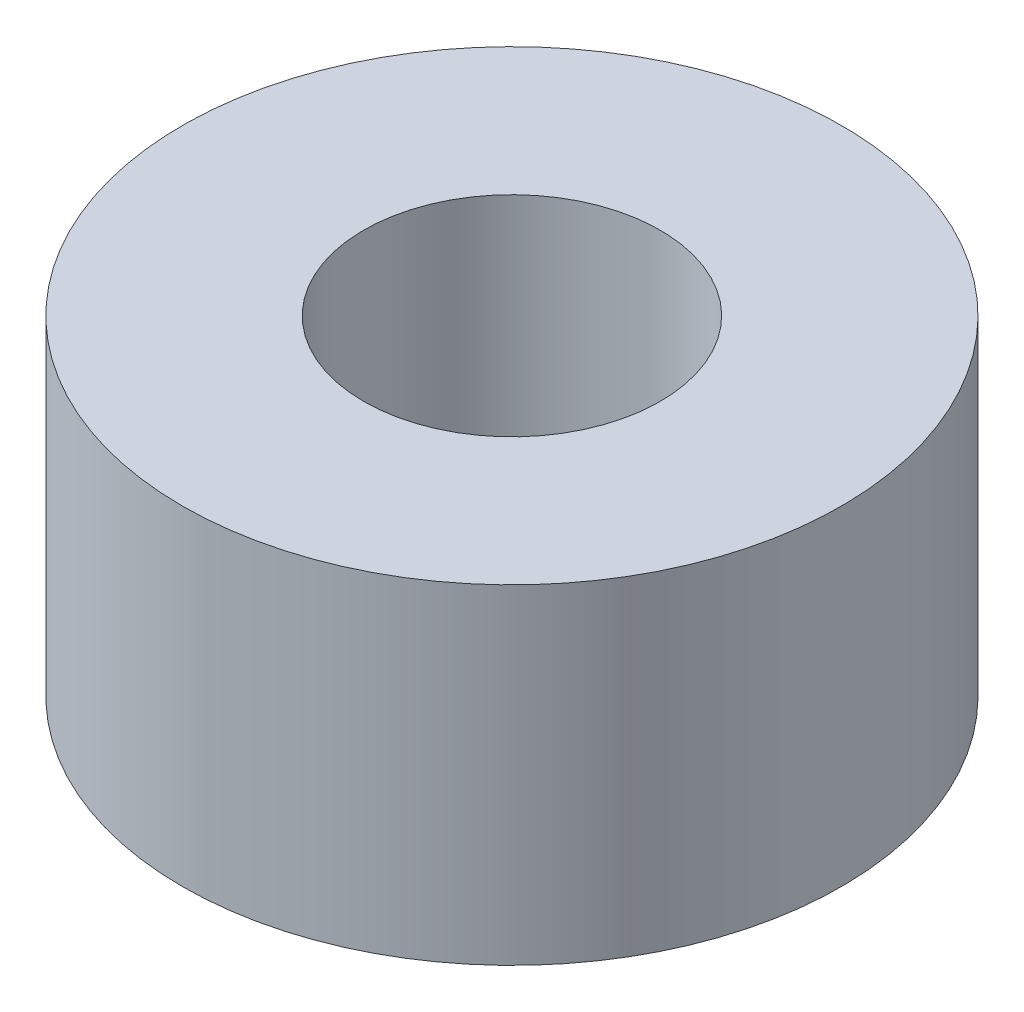
SolidWorks part; units mm, degrees
ref_plane "Front Plane" through (0, 0, 0) normal (0, 0, 1) x (1, 0, 0)
ref_plane "Top Plane" through (0, 0, 0) normal (0, 1, 0) x (1, 0, 0)
ref_plane "Right Plane" through (0, 0, 0) normal (1, 0, 0) x (0, 0, -1)
sketch "Sketch1" plane through (0, 0, 0) normal (0, 1, 0) x (1, 0, 0)
  circle A0 centre (0, 0) radius 4
  circle A1 centre (0, 0) radius 1.8
  dimension "D1" = 3.6
  dimension "D2" = 8
extrude "Boss-Extrude1" add sketch "Sketch1" along normal blind 4
